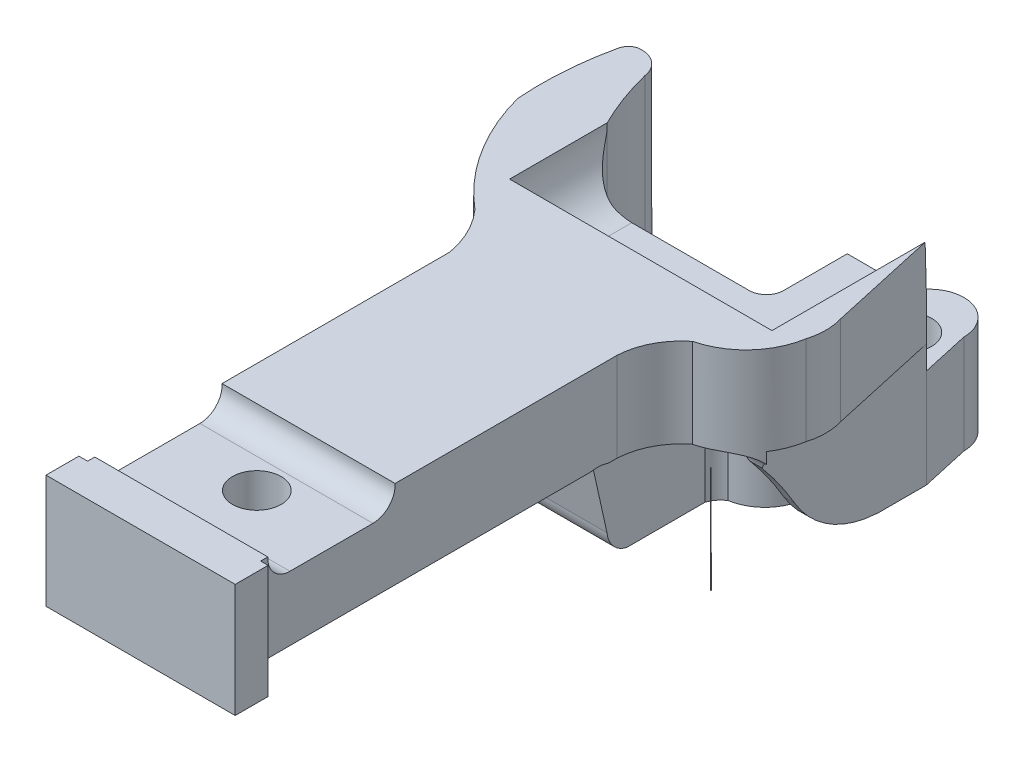
SolidWorks part; units mm, degrees
ref_plane "Front Plane" through (0, 0, 0) normal (0, 0, 1) x (1, 0, 0)
ref_plane "Top Plane" through (0, 0, 0) normal (0, 1, 0) x (1, 0, 0)
ref_plane "Right Plane" through (0, 0, 0) normal (1, 0, 0) x (0, 0, -1)
ref_plane "Plane1" through (0, 0, 0) normal (0, 1, 0) x (1, 0, 0)
sketch "Sketch2" plane through (0, 0, 0) normal (0, 1, 0) x (1, 0, 0)
  line L0 (0, 0) -> (-181.1731, 0) construction
  line L1 (0, 0) -> (181.1731, 0) construction
  line L2 (0, 0) -> (0, 174.625) construction
  line L3 (0, 174.625) -> (38.3822, 174.625) construction
  line L4 (38.3822, 174.625) -> (38.3822, 95.9485) construction
  line L5 (-79.2443, 0) -> (55.4409, 0)
  line L6 (74.468, 16.4026) -> (74.468, 72.8277)
  line L7 (0, 0) -> (0, -177.8046) construction
  line L8 (165.6666, 48.5518) -> (105.961, 48.5518) construction
  line L9 (181.1731, -30.2333) -> (145.0241, 132.5819)
  line L10 (-79.2443, -171.9521) -> (-79.2443, -544.4788)
  line L11 (-79.2443, -544.4788) -> (-88.2069, -544.4788)
  line L12 (-88.2069, -544.4788) -> (-88.2069, -578.3324)
  line L13 (-88.2069, -578.3324) -> (106.4078, -578.3324)
  line L14 (106.4078, -578.3324) -> (106.4078, -544.4788)
  line L15 (106.4078, -544.4788) -> (98.7308, -544.4788)
  line L16 (98.7308, -544.4788) -> (98.7308, -177.8046)
  line L17 (74.468, 72.8277) -> (74.468, 132.5819)
  line L18 (74.468, 132.5819) -> (145.0241, 132.5819) construction
  arc A0 (55.4409, 0) -> (74.468, 16.4026) centre (56.6714, 17.8097) ccw
  arc A5 (-79.2443, 0) -> (-113.1782, 23.6203) centre (-79.2443, 36.1856) cw
  arc A6 (98.7308, -177.8046) -> (125.1849, -126.6021) centre (168.2294, -181.2765) cw
  arc A7 (125.1849, -126.6021) -> (181.1731, -66.1354) centre (107.198, -53.7934) ccw
  arc A8 (181.1731, -66.1354) -> (181.1731, -30.2333) centre (121.7842, -48.1844) ccw
  arc A11 (-181.1731, 0) -> (-174.3141, 95.9485) centre (141.9049, 25.1237) cw
  arc A12 (-79.2443, -171.9521) -> (-104.3995, -120.9334) centre (-180.0191, -189.9291) ccw
  arc A13 (-104.3995, -120.9334) -> (-181.1731, 0) centre (47.1953, 60.1417) cw
  arc A14 (-113.1782, 23.6203) -> (-136.055, 85.4013) centre (155.9576, 158.4041) cw
  arc A15 (-136.055, 85.4013) -> (-163.9214, 106.7615) centre (-160.7266, 82.0721) ccw
  arc A16 (-174.3141, 95.9485) -> (-163.9214, 106.7615) centre (-160.803, 93.3634) cw
  arc A17 (74.468, 132.5819) -> (145.0241, 132.5819) centre (109.746, 132.5819) cw
extrude "Boss-Extrude1" add sketch "Sketch2" along normal blind 431.8
ref_plane "Plane2" through (0, 0, 0) normal (1, 0, 0) x (0, 0, -1)
sketch "Sketch3" plane through (0, 0, 0) normal (1, 0, 0) x (0, 0, -1)
  line L0 (-578.3324, 215.9) -> (-544.4788, 215.9) construction
  line L2 (-578.3324, 431.8) -> (-578.3324, 0) construction
  line L3 (-544.4788, 431.8) -> (-544.4788, 0) construction
  line L4 (-544.4788, 215.9) -> (-177.8046, 215.9) construction
  line L5 (-177.8046, 431.8) -> (-177.8046, 0) construction
  line L6 (-177.8046, 215.9) -> (-126.6021, 215.9) construction
  line L7 (-126.6021, 431.8) -> (-126.6021, 0) construction
  line L8 (-177.8046, 215.9) -> (-177.8046, 304.8) construction
  line L9 (-177.8046, 215.9) -> (-177.8046, 127) construction
  line L10 (-204.2811, 127) -> (-544.4788, 127)
  line L11 (-544.4788, 127) -> (-544.4788, 100.5284)
  line L12 (-544.4788, 431.8) -> (-544.4788, 0) construction
  line L13 (-544.4788, 100.5284) -> (-578.3324, 100.5284)
  line L14 (-578.3324, 100.5284) -> (-578.3324, 0)
  line L15 (-578.3324, 0) -> (-126.6021, 0)
  line L16 (-204.2811, 304.8) -> (-544.4788, 304.8)
  line L17 (-544.4788, 304.8) -> (-544.4788, 331.6689)
  line L18 (-544.4788, 331.6689) -> (-578.3324, 331.6689)
  line L19 (-578.3324, 331.6689) -> (-578.3324, 431.8)
  line L20 (-578.3324, 431.8) -> (-126.6021, 431.8)
  line L21 (-164.1658, 331.6689) -> (-146.9735, 411.8995)
  line L22 (-164.1658, 100.5284) -> (-146.9735, 23.1243)
  arc A0 (-204.2811, 127) -> (-164.1658, 100.5284) centre (-197.9023, 93.0352) cw
  arc A1 (-204.2811, 304.8) -> (-164.1658, 331.6689) centre (-212.5305, 360.4969) ccw
  arc A2 (-146.9735, 23.1243) -> (-126.6021, 0) centre (-120.9886, 25.4805) ccw
  arc A3 (-146.9735, 411.8995) -> (-126.6021, 431.8) centre (-126.0304, 410.8378) cw
extrude "Cut-Extrude1" cut sketch "Sketch3" against normal blind 190.5 and the other way blind 190.5
ref_plane "Plane3" through (0, 431.8, 0) normal (0, 1, 0) x (1, 0, 0)
sketch "Sketch4" plane through (0, 431.8, 0) normal (0, 1, 0) x (1, 0, 0)
  line L0 (155.8456, -87.211) -> (155.8456, 83.8419)
  line L1 (57.3181, -164.1658) -> (57.3181, -47.1303)
  line L2 (181.1731, -30.2333) -> (145.0241, 132.5819) construction
  line L3 (155.8456, -87.211) -> (177.8769, -101.3741)
  line L4 (177.8769, -101.3741) -> (226.395, -1.6845)
  line L5 (226.395, -1.6845) -> (155.8456, 83.8419)
  line L6 (144.698, -87.211) -> (144.698, 0)
  line L7 (130.535, 10.3565) -> (106.0505, 10.3565)
  line L9 (100.7806, -164.1658) -> (-80.9485, -164.1658) construction
  line L10 (144.698, -87.211) -> (138.6162, -92.6873)
  line L11 (138.6162, -92.6873) -> (138.6162, -164.1658)
  line L13 (-174.3141, 95.9485) -> (-160.803, 93.3634)
  line L14 (-67.5016, -54.3052) -> (-67.5016, -164.1658)
  line L16 (-106.0749, -164.1658) -> (-212.544, 0)
  line L17 (-212.544, 0) -> (-212.544, 95.9485)
  line L18 (-212.544, 95.9485) -> (-174.3141, 95.9485)
  line L19 (57.3181, -164.1658) -> (57.3181, -204.2811)
  line L20 (98.7308, -204.2811) -> (-79.2443, -204.2811) construction
  line L21 (57.3181, -204.2811) -> (138.6162, -204.2811)
  line L22 (138.6162, -204.2811) -> (138.6162, -164.1658)
  line L23 (-67.5016, -164.1658) -> (-67.5016, -204.2811)
  line L24 (-67.5016, -204.2811) -> (-94.8078, -204.2811)
  line L25 (-94.8078, -204.2811) -> (-106.0749, -164.1658)
  arc A0 (144.698, 0) -> (130.535, 10.3565) centre (124.7059, -12.4777) ccw
  arc A1 (-174.3141, 95.9485) -> (-181.1731, 0) centre (141.9049, 25.1237) ccw construction
  arc A2 (57.3181, -47.1303) -> (67.7738, -33.6872) centre (80.8109, -54.6149) cw
  arc A3 (67.7738, -33.6872) -> (106.0505, 10.3565) centre (60.1507, 11.592) ccw
  arc A4 (-163.9214, 106.7615) -> (-174.3141, 95.9485) centre (-160.803, 93.3634) ccw construction
  arc A5 (-160.803, 93.3634) -> (-146.9419, 64.7459) centre (-187.5705, 62.7327) cw
  arc A6 (-131.8856, 11.592) -> (-84.566, -26.667) centre (-57.7433, 54.9005) ccw
  arc A7 (-131.8856, 11.592) -> (-146.9419, 64.7459) centre (119.4804, 111.5026) cw
  arc A8 (-84.566, -26.667) -> (-67.5016, -54.3052) centre (-94.8078, -52.0775) cw
extrude "Cut-Extrude2" cut sketch "Sketch4" against normal blind 125.73
ref_plane "Plane4" through (0, 0, 0) normal (0, 0, 1) x (1, 0, 0)
sketch "Sketch6" plane through (0, 0, 0) normal (0, 0, 1) x (1, 0, 0)
  line L0 (-146.9419, 306.07) -> (-146.9419, 431.8) construction
  line L1 (-160.803, 306.07) -> (-160.803, 431.8) construction
  line L2 (-181.1731, 306.07) -> (-200.2867, 306.07)
  line L3 (-200.2867, 306.07) -> (-200.2867, 431.8)
  line L4 (201.2864, 431.8) -> (-201.2864, 431.8) construction
  line L5 (-200.2867, 431.8) -> (-84.566, 431.8)
  line L6 (-88.2069, 216.0987) -> (106.4078, 216.0987) construction
  line L7 (-88.2069, 331.6689) -> (-88.2069, 100.5284) construction
  line L8 (106.4078, 331.6689) -> (106.4078, 100.5284) construction
  line L9 (-181.1731, 126.1273) -> (-200.2867, 126.1273)
  line L11 (-200.2867, 126.1273) -> (-200.2867, 0.3973)
  line L12 (-200.2867, 0.3973) -> (-200.2867, -9.3355)
  line L13 (-200.2867, -9.3355) -> (-84.566, -9.3355)
  line L14 (-84.566, -9.3355) -> (-84.566, 0.3973)
  arc A0 (-84.566, 431.8) -> (-146.9419, 368.935) centre (-59.7662, 344.8155) ccw
  arc A1 (-181.1731, 306.07) -> (-160.803, 334.9279) centre (-210.7247, 348.5482) ccw
  arc A2 (-160.803, 334.9279) -> (-146.9419, 368.935) centre (-222.3693, 379.8504) ccw
  arc A3 (-181.1731, 126.1273) -> (-160.803, 97.2695) centre (-210.7247, 83.6492) cw
  arc A4 (-160.803, 97.2695) -> (-146.9419, 63.2623) centre (-222.3693, 52.3469) cw
  arc A5 (-84.566, 0.3973) -> (-146.9419, 63.2623) centre (-59.7662, 87.3819) cw
extrude "Cut-Extrude4" cut sketch "Sketch6" against normal blind 120.65 and the other way blind 128.27
sketch "Sketch7" plane through (0, 0, 0) normal (0, 1, 0) x (1, 0, 0)
  line L0 (156.0495, -86.3089) -> (156.0495, 84.7441)
  line L1 (57.522, -163.2636) -> (57.522, -46.2281)
  line L2 (156.0495, -86.3089) -> (178.0809, -100.4719)
  line L3 (178.0809, -100.4719) -> (226.5989, -0.7824)
  line L4 (226.5989, -0.7824) -> (156.0495, 84.7441)
  line L5 (144.9019, -86.3089) -> (144.9019, 0.9022)
  line L6 (130.7389, 11.2586) -> (106.2545, 11.2586)
  line L7 (144.9019, -86.3089) -> (138.8201, -91.7852)
  line L8 (138.8201, -91.7852) -> (138.8201, -163.2636)
  line L9 (-174.1102, 96.8507) -> (-160.5991, 94.2656)
  line L10 (-67.2977, -53.403) -> (-67.2977, -163.2636)
  line L11 (-105.871, -163.2636) -> (-212.3401, 0.9022)
  line L12 (-212.3401, 0.9022) -> (-212.3401, 96.8507)
  line L13 (-212.3401, 96.8507) -> (-174.1102, 96.8507)
  line L14 (57.522, -163.2636) -> (57.522, -203.3789)
  line L15 (57.522, -203.3789) -> (138.8201, -203.3789)
  line L16 (138.8201, -203.3789) -> (138.8201, -163.2636)
  line L17 (-67.2977, -163.2636) -> (-67.2977, -203.3789)
  line L18 (-67.2977, -203.3789) -> (-94.6039, -203.3789)
  line L19 (-94.6039, -203.3789) -> (-105.871, -163.2636)
  arc A0 (144.9019, 0.9022) -> (130.7389, 11.2586) centre (124.9098, -11.5755) ccw
  arc A1 (57.522, -46.2281) -> (67.9777, -32.7851) centre (81.0149, -53.7127) cw
  arc A2 (67.9777, -32.7851) -> (106.2545, 11.2586) centre (60.3547, 12.4942) ccw
  arc A3 (-160.5991, 94.2656) -> (-146.7379, 65.6481) centre (-187.3665, 63.6349) cw
  arc A4 (-131.6817, 12.4942) -> (-84.3621, -25.7648) centre (-57.5394, 55.8026) ccw
  arc A5 (-131.6817, 12.4942) -> (-146.7379, 65.6481) centre (119.6844, 112.4048) cw
  arc A6 (-84.3621, -25.7648) -> (-67.2977, -53.403) centre (-94.6039, -51.1753) cw
extrude "Cut-Extrude5" cut sketch "Sketch7" along normal blind 125.73
sketch "Sketch8" plane through (0, 0, 0) normal (1, 0, 0) x (0, 0, -1)
  line L0 (167.8599, 215.9) -> (167.8599, 330.2) construction
  line L1 (167.8599, 0) -> (167.8599, 431.8) construction
  line L2 (167.8599, 215.9) -> (167.8599, 101.6)
  line L3 (167.8599, 101.6) -> (82.9234, 101.6)
  line L4 (82.9234, 0) -> (82.9234, 125.73) construction
  line L5 (82.9234, 101.6) -> (83.8419, 330.2)
  line L6 (83.8419, 306.07) -> (83.8419, 431.8) construction
  line L7 (83.8419, 330.2) -> (167.8599, 330.2)
  line L8 (167.8599, 215.9) -> (167.8599, 330.2)
extrude "Cut-Extrude7" cut sketch "Sketch8" along normal blind 161.29
ref_plane "Plane5" through (177.8, 0, 0) normal (1, 0, 0) x (0, 0, -1)
sketch "Sketch9" plane through (177.8, 0, 0) normal (1, 0, 0) x (0, 0, -1)
  line L0 (-87.211, 306.07) -> (-87.211, 431.8) construction
  line L1 (201.2864, 431.8) -> (-201.2864, 431.8) construction
  line L2 (31.1301, 431.8) -> (31.1301, 493.4056)
  line L3 (31.1301, 493.4056) -> (-121.7481, 493.4056)
  line L4 (-121.7481, 493.4056) -> (-121.8928, 306.07)
  line L5 (106.9673, 216.0987) -> (-177.8046, 215.9) construction
  line L6 (106.9673, 97.1645) -> (106.9673, 335.0328) construction
  line L7 (-177.8046, 306.07) -> (-177.8046, 125.73) construction
  line L8 (-121.3609, -61.5271) -> (-121.7671, 125.8081)
  line L9 (31.517, -61.3138) -> (-121.3609, -61.5271)
  line L10 (31.4311, 0.2917) -> (31.517, -61.3138)
  arc A0 (-121.8928, 306.07) -> (-87.211, 331.3299) centre (-121.7481, 342.3102) ccw
  arc A1 (31.1301, 431.8) -> (-52.5498, 380.5393) centre (36.8707, 328.4973) ccw
  arc A2 (-87.211, 331.3299) -> (-52.5498, 380.5393) centre (-353.3735, 555.6165) ccw
  arc A3 (31.4311, 0.2917) -> (-52.3202, 51.4356) centre (37.0276, 103.6023) cw
  arc A4 (-87.0501, 100.5966) -> (-52.3202, 51.4356) centre (-352.8994, -124.0611) cw
  arc A5 (-121.7671, 125.8081) -> (-87.0501, 100.5966) centre (-121.5717, 89.5681) cw
extrude "Cut-Extrude8" cut sketch "Sketch9" against normal blind 45.72
sketch "Sketch10" plane through (0, 0, 0) normal (1, 0, 0) x (0, 0, -1)
  line L0 (-544.4788, 216.0987) -> (-177.8046, 215.9) construction
  line L1 (-544.4788, 331.6689) -> (-544.4788, 100.5284) construction
  line L2 (-177.8046, 306.07) -> (-177.8046, 125.73) construction
  line L3 (-514.3219, 216.0823) -> (-514.3219, 237.6695) construction
  line L4 (-514.3219, 237.6695) -> (-471.6464, 237.6695) construction
  line L5 (-471.6464, 237.6695) -> (-471.6464, 216.0592) construction
  line L6 (-428.9708, 216.0361) -> (-514.3219, 216.0823) construction
  line L7 (-428.9832, 193.2296) -> (-514.3342, 193.2758)
  line L8 (-428.9585, 238.8426) -> (-514.3095, 238.8888)
  arc A0 (-428.9832, 193.2296) -> (-428.9585, 238.8426) centre (-428.9708, 216.0361) ccw
  arc A1 (-514.3095, 238.8888) -> (-514.3342, 193.2758) centre (-514.3219, 216.0823) ccw
  point P11 (-471.6464, 216.0592)
extrude "Cut-Extrude9" cut sketch "Sketch10" against normal blind 88.9 and the other way blind 104.14
sketch "Sketch12" plane through (0, 0, 0) normal (0, 1, 0) x (1, 0, 0)
  circle A1 centre (111.8124, 107.6562) radius 25
extrude "Cut-Extrude10" cut sketch "Sketch12" along normal blind 431.8
sketch "Sketch13" plane through (0, 0, 0) normal (0, 0, 1) x (1, 0, 0)
  line L0 (197.3307, 215.9633) -> (197.3307, 266.7633) construction
  line L1 (197.3307, 215.9633) -> (197.3307, 165.1633) construction
  line L2 (156.7935, 266.7633) -> (-63.9981, 266.7633)
  line L3 (155.9928, 165.1633) -> (-63.9981, 165.1633)
  line L5 (197.3307, 215.9633) -> (-113.1782, 216.0987) construction
  line L6 (-113.1782, 417.8121) -> (-113.1782, 14.3853) construction
  line L7 (156.7935, 266.7633) -> (155.9928, 165.1633)
  line L8 (155.8671, 306.07) -> (156.0495, 101.6) construction
  arc A0 (-63.9981, 266.7633) -> (-63.9981, 165.1633) centre (-62.6772, 215.9633) ccw
extrude "Cut-Extrude11" cut sketch "Sketch13" against normal blind 88.9 and the other way blind 76.2
scale "Scale1" bodies to scale 113 110 scale about origin uniform scaling yes scale factor 0.05
sketch "Sketch15" plane through (0, 0, 28.9166) normal (0, 0, 1) x (1, 0, 0)
  line L0 (-19.4103, 10.8698) -> (25.5897, 10.8698)
  line L3 (-19.4103, 10.8698) -> (-19.4103, 47.6628)
  line L4 (-19.4103, 47.6628) -> (25.5897, 45.6428)
  line L5 (25.5897, 45.6428) -> (25.5897, 10.8698)
extrude "Cut-Extrude14" cut sketch "Sketch15" against normal blind 80 and the other way blind 10
sketch "Sketch17" plane through (0, 6.35, 0) normal (0, -1, 0) x (1, 0, 0)
  line L0 (0.4872, 27.2239) -> (0.4872, 10.2141) construction
  line L1 (4.9365, 27.2239) -> (-3.9622, 27.2239) construction
  line L2 (4.9365, 10.2141) -> (-3.9622, 10.2141) construction
  line L3 (0.4872, 10.2141) -> (0.4872, 18.719) construction
  line L4 (0.4872, 18.719) -> (0.4872, 27.2239) construction
  circle A0 centre (0.4872, 22.9715) radius 1.25
extrude "Cut-Extrude16" cut sketch "Sketch17" against normal blind 10
